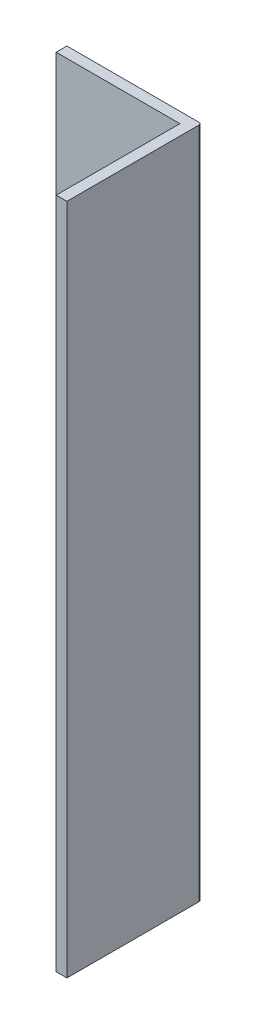
SolidWorks part; units mm, degrees
ref_plane "Alzado" through (0, 0, 0) normal (0, 0, 1) x (1, 0, 0)
ref_plane "Planta" through (0, 0, 0) normal (0, 1, 0) x (1, 0, 0)
ref_plane "Vista lateral" through (0, 0, 0) normal (1, 0, 0) x (0, 0, -1)
sketch "Croquis1" plane through (0, 0, 0) normal (0, 1, 0) x (1, 0, 0)
  line L0 (-23, 23) -> (0, 23)
  line L1 (0, 0) -> (0, 23)
  line L2 (-23, 25) -> (1.5, 25)
  line L3 (2, 0) -> (2, 24.5)
  line L4 (-23, 25) -> (-23, 23)
  line L5 (0, 0) -> (2, 0)
  line L6 (-23, 25) -> (2, 25) construction
  line L7 (2, 0) -> (2, 25) construction
  arc A0 (1.5, 25) -> (2, 24.5) centre (1.5, 24.5) cw
  dimension "D4" = 0.5
  dimension "D1" = 23
  dimension "D2" = 23
  dimension "D3" = 2
extrude "Saliente-Extruir1" add sketch "Croquis1" along normal blind 125
